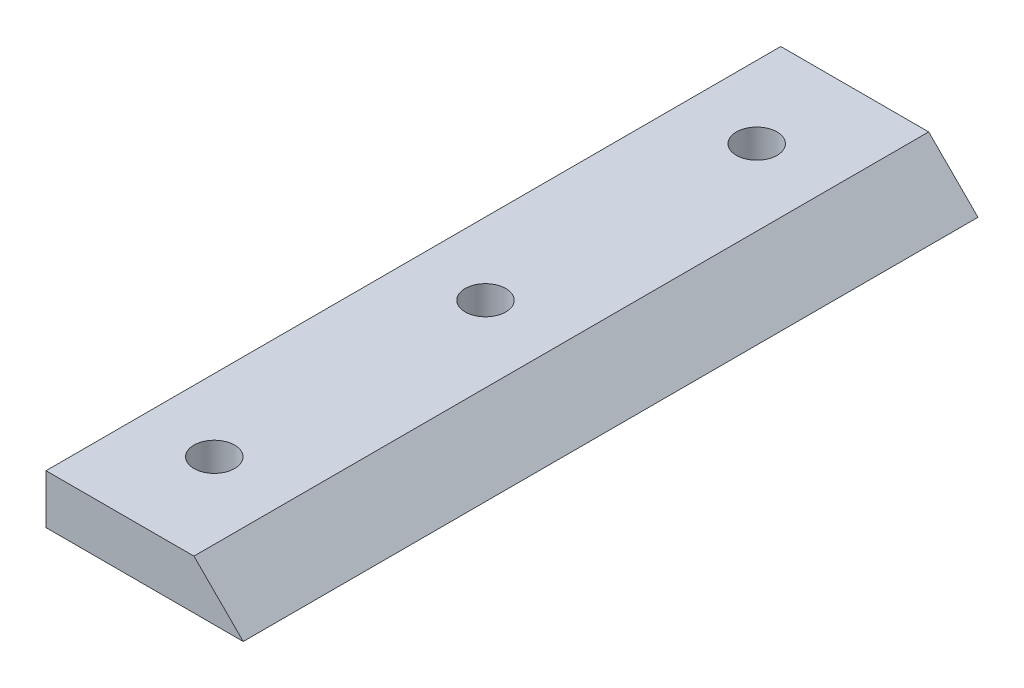
SolidWorks part; units mm, degrees
ref_plane "Front" through (0, 0, 0) normal (0, 0, 1) x (1, 0, 0)
ref_plane "Top" through (0, 0, 0) normal (0, 1, 0) x (1, 0, 0)
ref_plane "Right" through (0, 0, 0) normal (1, 0, 0) x (0, 0, -1)
sketch "Sketch1" plane through (0, 0, 0) normal (0, 0, 1) x (1, 0, 0)
  line L0 (-20, 10) -> (10, 10)
  line L1 (10, 10) -> (20, 0)
  line L2 (20, 0) -> (-20, 0)
  line L3 (-20, 0) -> (-20, 10)
  point P2 (9.7172, 8.6371)
  point P6 (0, 0)
  dimension "D1" = 10
  dimension "D2" = 40
  dimension "D3" = 30
extrude "Boss-Extrude1" add sketch "Sketch1" along normal mid plane 149
sketch "Sketch2" plane through (0, 10, 0) normal (0, 1, 0) x (1, 0, 0)
  line L0 (-20, -74.5) -> (-20, 74.5) construction
  line L1 (-50, 0) -> (50, 0) construction
  line L2 (0, 0) -> (-41.0797, 0) construction
  circle A0 centre (-5.375, 0) radius 4.125
  circle A1 centre (-5.375, -55) radius 4.125
  circle A2 centre (-5.375, 55) radius 4.125
  point P13 (0, 0)
  dimension "D1" = 8.25
  dimension "D3" = 110
  dimension "D2" = 10.5
extrude "Cut-Extrude1" cut sketch "Sketch2" against normal through all
